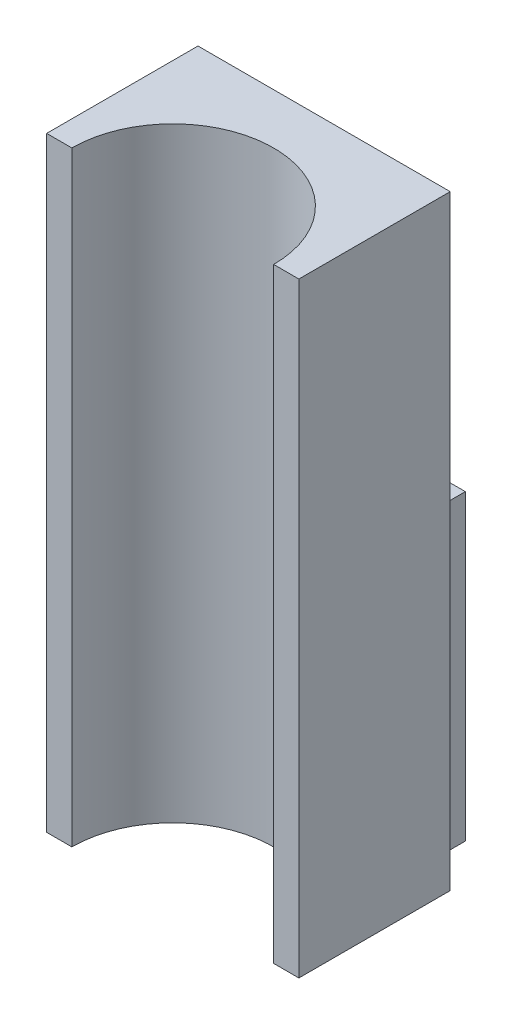
SolidWorks part; units mm, degrees
ref_plane "Front Plane" through (0, 0, 0) normal (0, 0, 1) x (1, 0, 0)
ref_plane "Top Plane" through (0, 0, 0) normal (0, 1, 0) x (1, 0, 0)
ref_plane "Right Plane" through (0, 0, 0) normal (1, 0, 0) x (0, 0, -1)
sketch "Sketch1" plane through (0, 0, 0) normal (0, 0, 1) x (1, 0, 0)
  line L5 (-3.6, 6) -> (3.6, 6)
  line L6 (-3.6, 6) -> (-3.6, -6)
  line L7 (-3.6, -6) -> (3.6, -6)
  line L8 (3.6, 6) -> (3.6, -6)
  line L9 (-3.6, 6) -> (3.6, -6) construction
  line L10 (-3.6, -6) -> (3.6, 6) construction
  point P0 (0, 0)
  dimension "D1" = 7.2
  dimension "D2" = 12
extrude "Boss-Extrude1" add sketch "Sketch1" along normal blind 2
sketch "Sketch2" plane through (0, 0, 2) normal (0, 0, 1) x (1, 0, 0)
  line L10 (3.6, 6) -> (-3.6, 6) construction
  line L11 (-5, 18) -> (5, 18)
  line L12 (-5, 18) -> (-5, -6)
  line L13 (-5, -6) -> (5, -6)
  line L14 (5, 18) -> (5, -6)
  line L15 (-5, 18) -> (5, -6) construction
  line L16 (-5, -6) -> (5, 18) construction
  point P0 (0, 6)
  dimension "D1" = 24
  dimension "D2" = 10
extrude "Boss-Extrude2" add sketch "Sketch2" along normal blind 6
sketch "Sketch5" plane through (0, 18, 0) normal (0, 1, 0) x (1, 0, 0)
  line L0 (5, -8) -> (-5, -8) construction
  line L1 (-4, -8) -> (4, -8)
  arc A0 (-4, -8) -> (4, -8) centre (0, -8) cw
  dimension "D1" = 4
extrude "Cut-Extrude1" cut sketch "Sketch5" against normal up to surface (24 mm away) up to face at (0, -6, 3)
equation "\"rail width\"= 24"
equation "\"system width\"= 125"
equation "\"system depth\"= 250"
equation "\"internal height\"= 100"
equation "\"carriage height\"= 24"
equation "\"belt width\"= 6"
equation "\"worm gear diameter\"= 8"
equation "\"motor mounting hole spacing\" = 35"
equation "\"motor hole radius\"= 4.2"
equation "\"motor diameter\"= 28"
equation "\"rotor shelf diameter\"= 9"
equation "\"rotor centre from motor centre\"= 8"
equation "\"pin radius\"= 2.7"
equation "\"pin spacing\"= 9"
equation "\"D1@Sketch1\"=\"belt width\"*1.2"
equation "\"D2@Sketch1\"=\"rail width\"/2"
equation "\"D1@Sketch2\"=\"rail width\""
equation "\"D2@Sketch2\"=\"worm gear diameter\"+2"
equation "\"D1@Sketch5\"=4"
